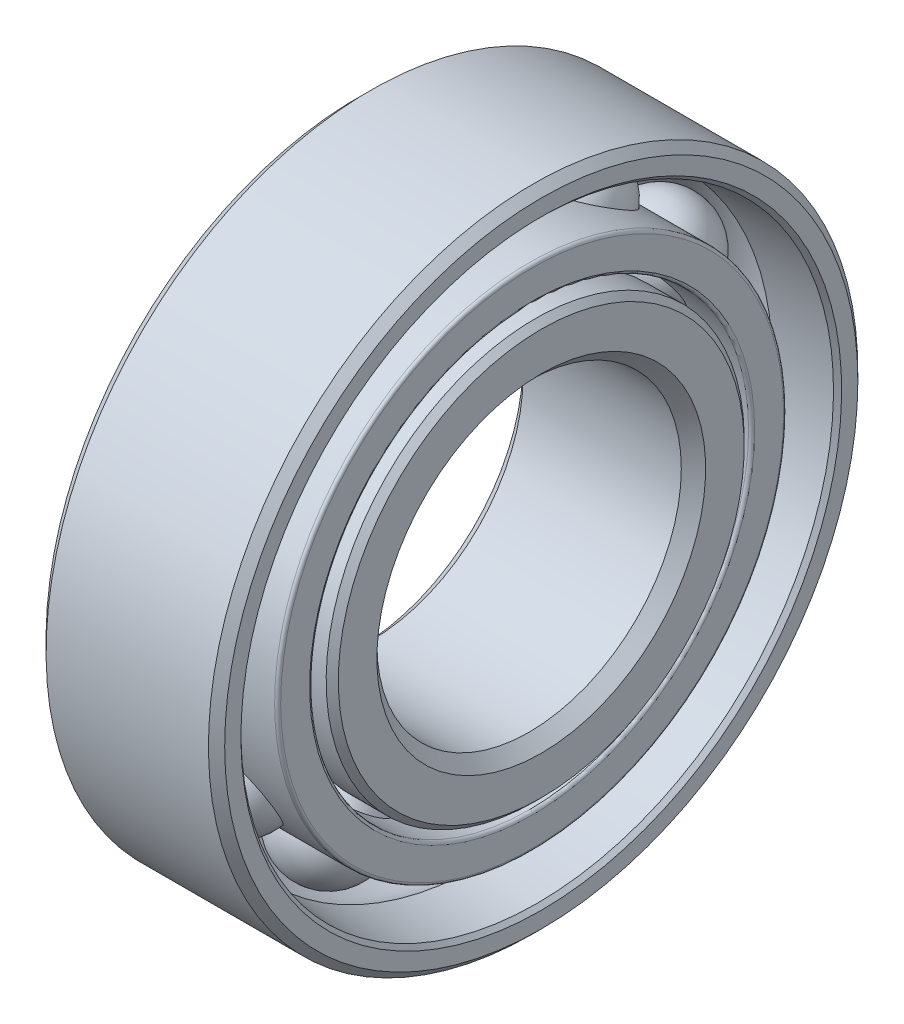
SolidWorks part; units mm, degrees
ref_plane "Front Plane" through (0, 0, 0) normal (0, 0, 1) x (1, 0, 0)
ref_plane "Top Plane" through (0, 0, 0) normal (0, 1, 0) x (1, 0, 0)
ref_plane "Right Plane" through (0, 0, 0) normal (1, 0, 0) x (0, 0, -1)
sketch "Sketch1" plane through (0, 0, 0) normal (1, 0, 0) x (0, 0, -1)
  line L0 (0, -16) -> (0, 16) construction
  line L1 (0, 13.2) -> (0, 10.3) construction
  line L2 (0, 10.3) -> (0, 8.7)
  line L3 (0, 13.2) -> (0, 14.8)
  circle A0 centre (0, 0) radius 16 construction
  circle A1 centre (0, 0) radius 14.8 construction
  circle A2 centre (0, 0) radius 7.5 construction
  circle A3 centre (0, 0) radius 13.2 construction
  circle A4 centre (0, 0) radius 10.3 construction
  circle A5 centre (0, 0) radius 8.7 construction
  circle A6 centre (0, 0) radius 0.3 construction
  circle A7 centre (0, 0) radius 0.2 construction
  point P9 (0, 0)
  point P11 (0, 14.8)
  point P15 (7.4, 12.8172)
  point P16 (12.8172, 7.4)
  point P17 (14.8, 0)
  point P18 (12.8172, -7.4)
  point P19 (7.4, -12.8172)
  point P20 (0, -14.8)
  point P21 (-7.4, -12.8172)
  point P22 (-12.8172, -7.4)
  point P23 (-14.8, 0)
  point P24 (0, 0)
  point P29 (-12.8172, 7.4)
  point P30 (0, 13.2)
  point P31 (0, 10.3)
  point P32 (0, 11.75)
  point P33 (-7.4, 12.8172)
  point P36 (0, 11.75)
  dimension "ID" = 15
  dimension "OD" = 32
  dimension "Back Side Inner Edge" = 29.6
  dimension "D1 Shoulder diameter of outer ring (large side face) " = 26.4
  dimension "d1 shoulder diameter of inner ring (Large side face) " = 20.6
  dimension "r1" = 0.3
  dimension "r3" = 0.2
  dimension "d2 shoulder diameter of inner ring (Small side face)" = 20.6
  dimension "r4" = 0.4
  dimension "r2" = 0.6
  dimension "Ball Bearing Count" = 12
sketch "Sketch2" plane through (0, 0, 0) normal (0, 0, 1) x (1, 0, 0)
  line L0 (-4.5, 0) -> (4.5, 0) construction
  line L1 (-4.5, -16) -> (4.5, -16) construction
  line L2 (4.5, 16) -> (-4.5, 16) construction
  line L3 (-4.5, -16) -> (-4.5, 16) construction
  line L4 (3.2, 0) -> (-1.0872, 16) construction
  line L5 (0, -16) -> (0, 16) construction
  line L6 (0, -16) -> (0, 16) construction
  line L7 (0, -14.8) -> (0, 14.8) construction
  line L9 (0, -13.2) -> (0, 13.2) construction
  circle A0 centre (0, 11.9426) radius 2.381 construction
  point P3 (0, 0)
  point P7 (0, -16)
  point P14 (0, 11.9426)
  point P15 (0, 14.8)
  point P16 (0, 16)
  point P20 (0, 13.2)
  point P24 (0, 10.3)
  point P28 (0, 8.7)
  point P29 (0, 7.5)
  point P33 (4.5, 16)
  point P35 (0, 16)
  point P36 (-4.5, 16)
  dimension "Ball Diameter" = 4.762
  dimension "a Distance from Side face to pressure point" = 7.7
  dimension "Width" = 9
sketch "Sketch3" plane through (0, 0, 0) normal (0, 0, 1) x (1, 0, 0)
  line L0 (0, -16) -> (0, 16) construction
  line L1 (0, -16) -> (0, 16) construction
  line L2 (4.1, 16) -> (-3.9, 16)
  line L3 (-4.5, 15.4) -> (-4.5, 13.2) construction
  line L4 (-4.5, -16) -> (-4.5, 16) construction
  line L5 (-4.5, 13.2) -> (-2.5659, 13.2) construction
  line L7 (4.5, 14.8) -> (0, 14.8) construction
  line L8 (4.5, 0) -> (4.5, 10.3) construction
  line L9 (3.9, 7.5) -> (-3.9, 7.5)
  line L13 (-4.5, 10.3) -> (-2.3381, 10.3) construction
  line L16 (4.5, 8.1) -> (4.5, 10.3) construction
  line L17 (-4.5, 8.1) -> (-4.5, 10.3) construction
  line L18 (2.3381, 10.3) -> (4.5, 10.3) construction
  line L19 (4.5, 0) -> (4.5, 14.8) construction
  line L20 (4.5, 14.6167) -> (1.5119, 14.3672) construction
  line L21 (4.5, 16) -> (-4.5, 16) construction
  line L22 (4.5, 8.1) -> (3.9, 7.5)
  line L26 (-4.5, 8.1) -> (-3.9, 7.5)
  line L27 (-3.9, 16) -> (-4.5, 15.4)
  line L28 (4.5, 14.6167) -> (4.5, 15.6) construction
  line L29 (4.1, 16) -> (4.5, 15.6)
  line L30 (-2.5659, 13.2) -> (-4.2, 13.2)
  line L32 (-4.5, 13.5) -> (-4.5, 15.4)
  line L33 (4.3, 14.6) -> (4.5, 14.8)
  line L34 (4.5, 15.6) -> (4.5, 14.8)
  line L35 (4.3, 14.6) -> (1.5119, 14.3672)
  line L36 (-4.5, 13.5) -> (-4.2, 13.2)
  line L37 (-2.3381, 10.3) -> (-4.2, 10.3)
  line L38 (-4.2, 10.3) -> (-4.5, 10)
  line L39 (-4.5, 10) -> (-4.5, 8.1)
  line L40 (2.3381, 10.3) -> (4.2, 10.3)
  line L41 (4.2, 10.3) -> (4.5, 10)
  line L42 (4.5, 10) -> (4.5, 8.1)
  circle A2 centre (0, 11.9426) radius 2.8574 construction
  arc A3 (-2.5659, 13.2) -> (0, 14.8) centre (0, 11.9426) cw
  arc A4 (-2.3381, 10.3) -> (2.3381, 10.3) centre (0, 11.9426) ccw
  arc A9 (0, 14.8) -> (1.5119, 14.3672) centre (0, 11.9426) cw
  point P6 (0, 16)
  point P18 (0, 7.5)
  point P26 (-1.5119, 14.3672)
  point P40 (-4.5, 7.5)
  dimension "D4" = 0.6
  dimension "D5" = 0.6
  dimension "D6" = 0.6
  dimension "D7" = 0.6
  dimension "D1" = 0.6
  dimension "D2" = 0.6
  dimension "D8" = 0.4
  dimension "D9" = 0.4
  dimension "D11" = 0.3
  dimension "D12" = 0.3
  dimension "D13" = 0.2
  dimension "D14" = 0.3
  dimension "D15" = 0.3
  dimension "D16" = 0.3
  dimension "D17" = 0.3
  dimension "D3" = 0.2
revolve "Revolve1" add sketch "Sketch3" angle 360 about L0
sketch "Sketch5" plane through (0, 0, 0) normal (0, 0, 1) x (1, 0, 0)
  line L0 (0, 14.3236) -> (0, 9.5616)
  arc A0 (0, 9.5616) -> (0, 14.3236) centre (0, 11.9426) ccw
  circle A1 centre (0, 11.9426) radius 2.381 construction
revolve "Revolve2" add sketch "Sketch5" angle 360 about L0
pattern_circular "CirPattern1" count 12 over 360 about axis through (0, 0, 0) along (1, 0, 0) of bodies 106
sketch "Sketch6" plane through (0, 0, 0) normal (1, 0, 0) x (0, 0, -1)
  circle A2 centre (0, 0) radius 10.815
  circle A3 centre (0, 0) radius 12.54
  dimension "D2" = 21.63
  dimension "D1" = 25.08
extrude "Boss-Extrude1" add sketch "Sketch6" along normal mid plane 8.1 separate body
sketch "Sketch8" plane through (0, 0, 0) normal (0, 0, 1) x (1, 0, 0)
  line L0 (0, 9.5516) -> (0, 14.3336)
  line L2 (0, 9.5616) -> (0, 14.3236) construction
  line L3 (-0.01, 9.5516) -> (-0.01, 14.3335) construction
  circle A0 centre (0, 11.9426) radius 2.381 construction
  arc A1 (0, 9.5616) -> (0, 14.3236) centre (0, 11.9426) ccw construction
  arc A2 (0, 9.5516) -> (0, 14.3336) centre (0, 11.9426) ccw
  arc A3 (-0.01, 9.5516) -> (-0.01, 14.3335) centre (0, 11.9426) ccw construction
  dimension "D1" = 0.01
revolve "Cut-Revolve1" cut sketch "Sketch8" angle 360 about L0
pattern_circular "CirPattern2" count 12 over 360 about axis through (0, 0, 0) along (1, 0, 0) of "Cut-Revolve1"
sketch "Sketch9" plane through (0, 0, 0) normal (0, 0, 1) x (1, 0, 0)
  line L1 (0, 11.9426) -> (3.2, 0)
  line L2 (3.2, 0) -> (-4.5, 0)
  line L3 (3.2, 0) -> (-1.0872, 16) construction
  line L4 (-4.5, 10.3) -> (-2.3381, 10.3) construction
  line L5 (2.3381, 10.3) -> (4.5, 10.3) construction
  line L6 (4.5, 14.6167) -> (1.5119, 14.3672) construction
  line L7 (-4.5, 13.2) -> (-2.5659, 13.2) construction
  line L8 (-4.5, 10.3) -> (-2.3381, 10.3)
  line L9 (2.3381, 10.3) -> (4.5, 10.3)
  line L10 (4.5, 14.6167) -> (1.5119, 14.3672)
  line L11 (-4.5, 13.2) -> (-2.5659, 13.2)
  circle A0 centre (0, 11.9426) radius 2.381 construction
  circle A1 centre (0, 11.9426) radius 2.381
  point P2 (0, 11.9426)
fillet "Fillet1" radius 0.15 4 edges at (4.05, 0, -10.815) (4.05, 0, -12.54) (-4.05, 0, -10.815) (-4.05, 0, -12.54)
equation "\"D1@CirPattern1\"=\"Ball Bearing Count@Sketch1\""
equation "\"D2@Sketch6\" = \"d1 shoulder diameter of inner ring (Large side face) @Sketch1\" * 1.050"
equation "\"D1@Sketch6\" = \"D1 Shoulder diameter of outer ring (large side face) @Sketch1\" * .950"
equation "\"D1@CirPattern2\"=\"Ball Bearing Count@Sketch1\""
equation "\"Back Side Inner Edge@Sketch1\"=\"OD@Sketch1\"-2.4"
equation "\"D4@Sketch3\"=\"r2@Sketch1\""
equation "\"D5@Sketch3\"=\"r2@Sketch1\""
equation "\"D6@Sketch3\"=\"r2@Sketch1\""
equation "\"D7@Sketch3\"=\"r2@Sketch1\""
equation "\"D1@Sketch3\"=\"r2@Sketch1\""
equation "\"D2@Sketch3\"=\"r2@Sketch1\""
equation "\"D8@Sketch3\"=\"r4@Sketch1\""
equation "\"D9@Sketch3\"=\"r4@Sketch1\""
equation "\"D1@Boss-Extrude1\"=\"Width@Sketch2\"*.90"
equation "\"D11@Sketch3\"=\"r1@Sketch1\""
equation "\"D12@Sketch3\"=\"r1@Sketch1\""
equation "\"D13@Sketch3\"=\"r3@Sketch1\""
equation "\"D14@Sketch3\"=\"r1@Sketch1\""
equation "\"D15@Sketch3\"=\"r1@Sketch1\""
equation "\"D16@Sketch3\"=\"r1@Sketch1\""
equation "\"D17@Sketch3\"=\"r1@Sketch1\""
equation "\"D3@Sketch3\"=\"r3@Sketch1\""
equation "\"D1@Fillet1\"=\"ID@Sketch1\"/100"
